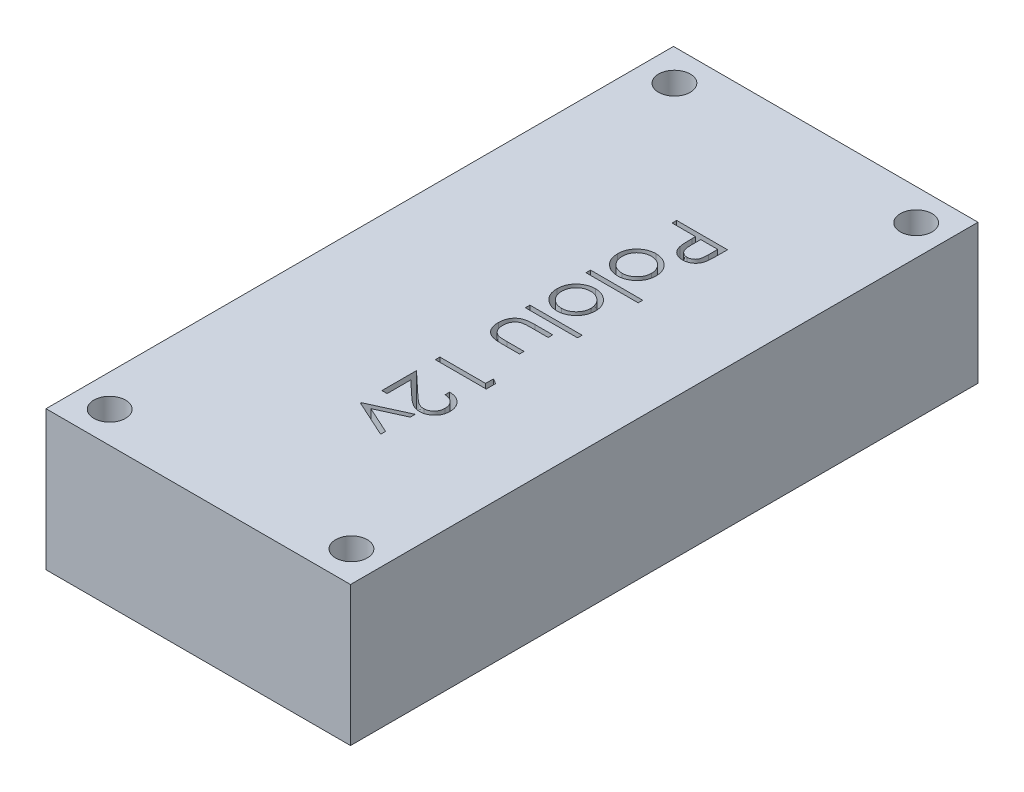
SolidWorks part; units mm, degrees
ref_plane "Front Plane" through (0, 0, 0) normal (0, 0, 1) x (1, 0, 0)
ref_plane "Top Plane" through (0, 0, 0) normal (0, 1, 0) x (1, 0, 0)
ref_plane "Right Plane" through (0, 0, 0) normal (1, 0, 0) x (0, 0, -1)
sketch "Sketch1" plane through (0, 0, 0) normal (0, 1, 0) x (1, 0, 0)
  line L1 (-10.4775, -21.59) -> (10.4775, -21.59)
  line L2 (-10.4775, -21.59) -> (-10.4775, 21.59)
  line L3 (-10.4775, 21.59) -> (10.4775, 21.59)
  line L4 (10.4775, -21.59) -> (10.4775, 21.59)
  line L5 (-10.4775, -21.59) -> (10.4775, 21.59) construction
  line L6 (-10.4775, 21.59) -> (10.4775, -21.59) construction
  point P0 (0, 0)
  dimension "D1" = 20.955
  dimension "D2" = 43.18
extrude "Boss-Extrude1" add sketch "Sketch1" along normal blind 9.6
sketch "Sketch2" plane through (0, 9.6, 0) normal (0, 1, 0) x (1, 0, 0)
  circle A0 centre (-8.255, 19.431) radius 1.0922
  circle A1 centre (8.382, 19.431) radius 1.0922
  circle A2 centre (8.382, -19.431) radius 1.0922
  circle A3 centre (-8.255, -19.431) radius 1.0922
  dimension "D1" = 2.1844
  dimension "D2" = 16.637
  dimension "D3" = 38.862
  dimension "D4" = 19.431
  dimension "D5" = 8.382
extrude "Cut-Extrude1" cut sketch "Sketch2" against normal through all
sketch "Sketch3" plane through (0, 9.6, 0) normal (0, 1, 0) x (1, 0, 0)
  line L0 (0, 21.59) -> (0, -21.59) construction
  line L1 (10.4775, 21.59) -> (-10.4775, 21.59) construction
  line L2 (-10.4775, -21.59) -> (10.4775, -21.59) construction
  text T0 "Pololu 12v"
extrude "Cut-Extrude2" cut sketch "Sketch3" against normal blind 2.54
